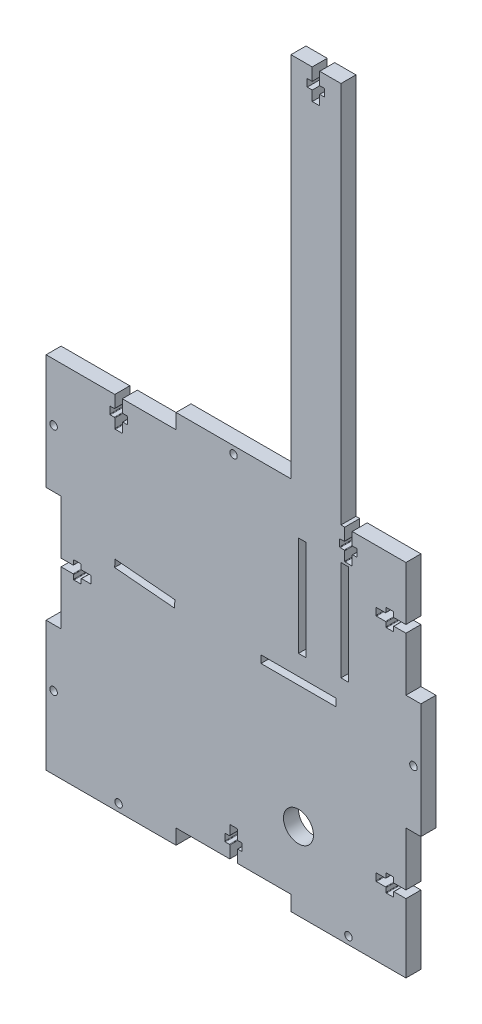
SolidWorks part; units mm, degrees
ref_plane "Front Plane" through (0, 0, 0) normal (0, 0, 1) x (1, 0, 0)
ref_plane "Top Plane" through (0, 0, 0) normal (0, 1, 0) x (1, 0, 0)
ref_plane "Right Plane" through (0, 0, 0) normal (1, 0, 0) x (0, 0, -1)
sketch "Sketch1" plane through (0, 0, 0) normal (0, 0, 1) x (1, 0, 0)
  line L0 (-69, 69) -> (-23, 69)
  line L5 (-75, -75) -> (75, -75) construction
  line L6 (-75, -75) -> (-75, 75) construction
  line L7 (-75, 75) -> (75, 75) construction
  line L8 (75, -75) -> (75, 75) construction
  line L9 (75, 23) -> (69, 23)
  line L10 (69, -23) -> (75, -23)
  line L11 (-69, -69) -> (69, -69) construction
  line L12 (-69, -69) -> (-69, 69) construction
  line L13 (-69, 69) -> (69, 69) construction
  line L14 (69, -69) -> (69, 69) construction
  line L15 (-69, -69) -> (69, 69) construction
  line L16 (69, -69) -> (69, -23)
  line L17 (-23, 69) -> (-23, 75)
  line L18 (-23, 75) -> (23, 75)
  line L19 (23, 75) -> (23, 69)
  line L20 (23, 69) -> (69, 69)
  line L21 (75, -23) -> (75, 23)
  line L22 (69, 23) -> (69, 69)
  line L23 (-75, 23) -> (-69, 23)
  line L24 (-69, 69) -> (-75, 69)
  line L25 (-75, 69) -> (-75, 23)
  line L26 (69, -69) -> (69, -75)
  line L27 (69, -75) -> (23, -75)
  line L28 (23, -75) -> (23, -69)
  line L29 (23, -69) -> (-23, -69)
  line L30 (-23, -69) -> (-23, -75)
  line L31 (-23, -75) -> (-69, -75)
  line L32 (-69, -75) -> (-69, -69) construction
  line L33 (-69, 23) -> (-69, -23)
  line L34 (-69, -23) -> (-75, -23)
  line L35 (-75, -23) -> (-75, -69)
  line L36 (-75, -69) -> (-69, -69) construction
  line L37 (-46, 69) -> (-46, -75) construction
  line L38 (-69, 69) -> (69, -69) construction
  line L39 (-75, -75) -> (-69, -75)
  line L40 (-75, -75) -> (-75, -69)
  point P0 (0, 0)
  point P6 (-7, -7)
  point P26 (0, -75)
  point P27 (-75, 0)
  dimension "D1" = 150
  dimension "D2" = 150
  dimension "D5" = 46
  dimension "D3" = 6
  dimension "D6" = 6
  dimension "D7" = 6
extrude "Box Side" add sketch "Sketch1" along normal blind 6
sketch "Sketch2" plane through (0, 0, 6) normal (0, 0, 1) x (1, 0, 0)
  line L0 (23, 72) -> (-23, 72) construction
  line L1 (23, 75) -> (23, 69) construction
  line L2 (-23, 69) -> (-23, 75) construction
  line L3 (-46, 69) -> (-46, -75) construction
  line L5 (0, 75) -> (0, 69) construction
  line L6 (-23, 75) -> (23, 75) construction
  line L7 (-69, 69) -> (69, 69) construction
  line L16 (-46, 69) -> (-46, -75) construction
  line L21 (0, -69) -> (0, 69) construction
  line L35 (-69, 69) -> (-23, 69) construction
  line L36 (-44.5, 69) -> (-44.5, 64.2)
  line L37 (-44.3, 64) -> (-42.7, 64)
  line L38 (-42.5, 63.8) -> (-42.5, 61.2)
  line L39 (-42.7, 61) -> (-44.3, 61)
  line L40 (-44.5, 60.8) -> (-44.5, 57.2)
  line L46 (-44.7, 57) -> (-47.3, 57)
  line L48 (-44.5, 69) -> (-47.5, 69)
  line L51 (-47.5, 60.8) -> (-47.5, 57.2)
  line L52 (-49.3, 61) -> (-47.7, 61)
  line L53 (-49.5, 63.8) -> (-49.5, 61.2)
  line L54 (-47.7, 64) -> (-49.3, 64)
  line L55 (-47.5, 69) -> (-47.5, 64.2)
  line L56 (47.5, 69) -> (47.5, 64.2)
  line L57 (47.7, 64) -> (49.3, 64)
  line L58 (49.5, 63.8) -> (49.5, 61.2)
  line L59 (49.3, 61) -> (47.7, 61)
  line L60 (47.5, 60.8) -> (47.5, 57.2)
  line L61 (44.5, 69) -> (47.5, 69)
  line L62 (44.7, 57) -> (47.3, 57)
  line L63 (44.5, 60.8) -> (44.5, 57.2)
  line L64 (42.7, 61) -> (44.3, 61)
  line L65 (42.5, 63.8) -> (42.5, 61.2)
  line L66 (44.3, 64) -> (42.7, 64)
  line L67 (44.5, 69) -> (44.5, 64.2)
  line L68 (-69, -69) -> (69, 69) construction
  line L69 (-69, -69) -> (69, 69) construction
  line L70 (75, 0) -> (69, 0) construction
  line L71 (72, 23) -> (72, -23) construction
  line L72 (69, 44.5) -> (64.2, 44.5)
  line L73 (64, 44.3) -> (64, 42.7)
  line L74 (63.8, 42.5) -> (61.2, 42.5)
  line L75 (61, 42.7) -> (61, 44.3)
  line L76 (60.8, 44.5) -> (57.2, 44.5)
  line L77 (57, 44.7) -> (57, 47.3)
  line L78 (69, 44.5) -> (69, 47.5)
  line L79 (60.8, 47.5) -> (57.2, 47.5)
  line L80 (61, 49.3) -> (61, 47.7)
  line L81 (63.8, 49.5) -> (61.2, 49.5)
  line L82 (64, 47.7) -> (64, 49.3)
  line L83 (69, 47.5) -> (64.2, 47.5)
  line L84 (69, -47.5) -> (64.2, -47.5)
  line L85 (64, -47.7) -> (64, -49.3)
  line L86 (63.8, -49.5) -> (61.2, -49.5)
  line L87 (61, -49.3) -> (61, -47.7)
  line L88 (60.8, -47.5) -> (57.2, -47.5)
  line L89 (69, -44.5) -> (69, -47.5)
  line L90 (57, -44.7) -> (57, -47.3)
  line L91 (60.8, -44.5) -> (57.2, -44.5)
  line L92 (61, -42.7) -> (61, -44.3)
  line L93 (63.8, -42.5) -> (61.2, -42.5)
  line L94 (64, -44.3) -> (64, -42.7)
  line L95 (69, -44.5) -> (64.2, -44.5)
  line L120 (-69, 69) -> (69, -69) construction
  line L121 (-69, 69) -> (69, -69) construction
  line L122 (-1.5, -69) -> (1.5, -69)
  line L123 (-23, -69) -> (23, -69) construction
  line L124 (1.5, -69) -> (1.5, -64.2)
  line L125 (1.7, -64) -> (3.3, -64)
  line L126 (3.5, -63.8) -> (3.5, -61.2)
  line L127 (3.3, -61) -> (1.7, -61)
  line L128 (1.5, -60.8) -> (1.5, -57.2)
  line L129 (1.3, -57) -> (-1.3, -57)
  line L130 (-1.5, -60.8) -> (-1.5, -57.2)
  line L131 (-3.3, -61) -> (-1.7, -61)
  line L132 (-3.5, -63.8) -> (-3.5, -61.2)
  line L133 (-1.7, -64) -> (-3.3, -64)
  line L134 (-1.5, -69) -> (-1.5, -64.2)
  line L135 (-69, -1.5) -> (-64.2, -1.5)
  line L136 (-64, -1.7) -> (-64, -3.3)
  line L137 (-63.8, -3.5) -> (-61.2, -3.5)
  line L138 (-61, -3.3) -> (-61, -1.7)
  line L139 (-60.8, -1.5) -> (-57.2, -1.5)
  line L140 (-57, 1.3) -> (-57, -1.3)
  line L141 (-60.8, 1.5) -> (-57.2, 1.5)
  line L142 (-61, 3.3) -> (-61, 1.7)
  line L143 (-63.8, 3.5) -> (-61.2, 3.5)
  line L144 (-64, 1.7) -> (-64, 3.3)
  line L145 (-69, 1.5) -> (-64.2, 1.5)
  line L146 (-69, -1.5) -> (-69, 1.5)
  line L147 (-69, -72) -> (-23, -72) construction
  line L148 (-23, 69) -> (-75, 69) construction
  line L149 (-23, -75) -> (-23, -69) construction
  line L150 (-69, -69) -> (-69, -75) construction
  line L151 (-75, -75) -> (-23, -75) construction
  circle A0 centre (0, 72) radius 1.5
  arc A1 (-44.5, 57.2) -> (-44.7, 57) centre (-44.7, 57.2) cw
  arc A2 (-44.3, 61) -> (-44.5, 60.8) centre (-44.3, 60.8) ccw
  arc A3 (-42.5, 61.2) -> (-42.7, 61) centre (-42.7, 61.2) cw
  arc A4 (-42.7, 64) -> (-42.5, 63.8) centre (-42.7, 63.8) cw
  arc A5 (-44.5, 64.2) -> (-44.3, 64) centre (-44.3, 64.2) ccw
  arc A6 (-47.5, 64.2) -> (-47.7, 64) centre (-47.7, 64.2) cw
  arc A7 (-49.3, 64) -> (-49.5, 63.8) centre (-49.3, 63.8) ccw
  arc A8 (-49.5, 61.2) -> (-49.3, 61) centre (-49.3, 61.2) ccw
  arc A9 (-47.7, 61) -> (-47.5, 60.8) centre (-47.7, 60.8) cw
  arc A10 (-47.5, 57.2) -> (-47.3, 57) centre (-47.3, 57.2) ccw
  arc A11 (47.5, 57.2) -> (47.3, 57) centre (47.3, 57.2) cw
  arc A12 (47.7, 61) -> (47.5, 60.8) centre (47.7, 60.8) ccw
  arc A13 (49.5, 61.2) -> (49.3, 61) centre (49.3, 61.2) cw
  arc A14 (49.3, 64) -> (49.5, 63.8) centre (49.3, 63.8) cw
  arc A15 (47.5, 64.2) -> (47.7, 64) centre (47.7, 64.2) ccw
  arc A16 (44.5, 64.2) -> (44.3, 64) centre (44.3, 64.2) cw
  arc A17 (42.7, 64) -> (42.5, 63.8) centre (42.7, 63.8) ccw
  arc A18 (42.5, 61.2) -> (42.7, 61) centre (42.7, 61.2) ccw
  arc A19 (44.3, 61) -> (44.5, 60.8) centre (44.3, 60.8) cw
  arc A20 (44.5, 57.2) -> (44.7, 57) centre (44.7, 57.2) ccw
  arc A21 (57.2, 44.5) -> (57, 44.7) centre (57.2, 44.7) cw
  arc A22 (61, 44.3) -> (60.8, 44.5) centre (60.8, 44.3) ccw
  arc A23 (61.2, 42.5) -> (61, 42.7) centre (61.2, 42.7) cw
  arc A24 (64, 42.7) -> (63.8, 42.5) centre (63.8, 42.7) cw
  arc A25 (64.2, 44.5) -> (64, 44.3) centre (64.2, 44.3) ccw
  arc A26 (64.2, 47.5) -> (64, 47.7) centre (64.2, 47.7) cw
  arc A27 (64, 49.3) -> (63.8, 49.5) centre (63.8, 49.3) ccw
  arc A28 (61.2, 49.5) -> (61, 49.3) centre (61.2, 49.3) ccw
  arc A29 (61, 47.7) -> (60.8, 47.5) centre (60.8, 47.7) cw
  arc A30 (57.2, 47.5) -> (57, 47.3) centre (57.2, 47.3) ccw
  arc A31 (57.2, -47.5) -> (57, -47.3) centre (57.2, -47.3) cw
  arc A32 (61, -47.7) -> (60.8, -47.5) centre (60.8, -47.7) ccw
  arc A33 (61.2, -49.5) -> (61, -49.3) centre (61.2, -49.3) cw
  arc A34 (64, -49.3) -> (63.8, -49.5) centre (63.8, -49.3) cw
  arc A35 (64.2, -47.5) -> (64, -47.7) centre (64.2, -47.7) ccw
  arc A36 (64.2, -44.5) -> (64, -44.3) centre (64.2, -44.3) cw
  arc A37 (64, -42.7) -> (63.8, -42.5) centre (63.8, -42.7) ccw
  arc A38 (61.2, -42.5) -> (61, -42.7) centre (61.2, -42.7) ccw
  arc A39 (61, -44.3) -> (60.8, -44.5) centre (60.8, -44.3) cw
  arc A40 (57.2, -44.5) -> (57, -44.7) centre (57.2, -44.7) ccw
  circle A41 centre (72, 0) radius 1.5
  arc A62 (1.5, -57.2) -> (1.3, -57) centre (1.3, -57.2) ccw
  arc A63 (1.7, -61) -> (1.5, -60.8) centre (1.7, -60.8) cw
  arc A64 (3.5, -61.2) -> (3.3, -61) centre (3.3, -61.2) ccw
  arc A65 (3.3, -64) -> (3.5, -63.8) centre (3.3, -63.8) ccw
  arc A66 (1.5, -64.2) -> (1.7, -64) centre (1.7, -64.2) cw
  arc A67 (-1.5, -64.2) -> (-1.7, -64) centre (-1.7, -64.2) ccw
  arc A68 (-3.3, -64) -> (-3.5, -63.8) centre (-3.3, -63.8) cw
  arc A69 (-3.5, -61.2) -> (-3.3, -61) centre (-3.3, -61.2) cw
  arc A70 (-1.7, -61) -> (-1.5, -60.8) centre (-1.7, -60.8) ccw
  arc A71 (-1.5, -57.2) -> (-1.3, -57) centre (-1.3, -57.2) cw
  arc A72 (-57.2, -1.5) -> (-57, -1.3) centre (-57.2, -1.3) ccw
  arc A73 (-61, -1.7) -> (-60.8, -1.5) centre (-60.8, -1.7) cw
  arc A74 (-61.2, -3.5) -> (-61, -3.3) centre (-61.2, -3.3) ccw
  arc A75 (-64, -3.3) -> (-63.8, -3.5) centre (-63.8, -3.3) ccw
  arc A76 (-64.2, -1.5) -> (-64, -1.7) centre (-64.2, -1.7) cw
  arc A77 (-64.2, 1.5) -> (-64, 1.7) centre (-64.2, 1.7) ccw
  arc A78 (-64, 3.3) -> (-63.8, 3.5) centre (-63.8, 3.3) cw
  arc A79 (-61.2, 3.5) -> (-61, 3.3) centre (-61.2, 3.3) cw
  arc A80 (-61, 1.7) -> (-60.8, 1.5) centre (-60.8, 1.7) ccw
  arc A81 (-57.2, 1.5) -> (-57, 1.3) centre (-57.2, 1.3) cw
  circle A82 centre (-46, -72) radius 1.5
  circle A83 centre (46, -72) radius 1.5
  circle A84 centre (-72, 46) radius 1.5
  circle A85 centre (-72, -46) radius 1.5
  point P6 (0, 72)
  point P38 (0, 0)
  point P56 (-46, 57)
  point P88 (46, 57)
  point P161 (57, 46)
  point P162 (57, -46)
  point P198 (0, -57)
  point P231 (-57, 0)
  point P234 (-42.5, 62.5)
  dimension "D1" = 3
  dimension "D2" = 0.2
  dimension "D8" = 0.2
  dimension "D14" = 3
  dimension "D4" = 3
  dimension "D7" = 1.5
  dimension "D10" = 3
  dimension "D12" = 1.5
  dimension "D9" = 12
  dimension "D11" = 5
  dimension "D13" = 7
  dimension "D3" = 12
  dimension "D5" = 7
  dimension "D6" = 5
extrude "Screw Cut-outs" cut sketch "Sketch2" against normal through all
sketch "Bearing Hole" plane through (0, 0, 6) normal (0, 0, 1) x (1, 0, 0)
  line L0 (20, -69) -> (50020, -69) construction
  line L1 (69, -44.5) -> (69, -23) construction
  line L4 (26, -41) -> (50026, -41) construction
  line L5 (26.5774, -47) -> (50026.5774, -47) construction
  line L8 (29, -52) -> (29, -50052) construction
  circle A0 centre (26, -44) radius 3 construction
  circle A1 centre (26, -54) radius 15 construction
  circle A2 centre (26, -44) radius 6
  dimension "D2" = 6
  dimension "D4" = 30
  dimension "D5" = 12
  dimension "D1" = 7
  dimension "D3" = 43
extrude "Shaft Hole" cut sketch "Bearing Hole" against normal through all
sketch "Sketch4" plane through (0, 0, 0) normal (0, 0, -1) x (-1, 0, 0)
  line L0 (-72, 1.5) -> (49928, 1.5) construction
  line L1 (-41, 8) -> (-11, 8)
  line L2 (-41, 8) -> (-41, 5)
  line L3 (-41, 5) -> (-11, 5)
  line L4 (-11, 8) -> (-11, 5)
  line L5 (-75, -23) -> (-75, 23) construction
  line L6 (-69, 23) -> (-69, 44.5) construction
  line L7 (-46, 56) -> (-43, 56)
  line L8 (-46, 56) -> (-46, 16)
  line L9 (-46, 16) -> (-43, 16)
  line L10 (-43, 56) -> (-43, 16)
  line L11 (-29, 56) -> (-26, 56)
  line L12 (-29, 56) -> (-29, 16)
  line L13 (-29, 16) -> (-26, 16)
  line L14 (-26, 56) -> (-26, 16)
  line L15 (-44.5, 69) -> (-23, 69) construction
  circle A1 centre (-72, 0) radius 1.5 construction
  point P18 (-29, 36)
  dimension "D1" = 3.5
  dimension "D2" = 30
  dimension "D3" = 3
  dimension "D4" = 34
  dimension "D5" = 14
  dimension "D6" = 23
  dimension "D7" = 13
  dimension "D8" = 3
  dimension "D9" = 40
extrude "Grooves" cut sketch "Sketch4" against normal up to surface (6 mm away) up to face at (32, -44, 6)
sketch "Sketch5" plane through (0, 69, 0) normal (0, 1, 0) x (1, 0, 0)
  line L0 (69, 0) -> (47.5, 0) construction
  line L1 (23, -6) -> (43, -6)
  line L2 (23, -6) -> (23, 0)
  line L3 (23, 0) -> (43, 0)
  line L4 (43, -6) -> (43, 0)
  line L5 (75, -6) -> (75, 0) construction
  dimension "D1" = 32
extrude "Boss-Extrude1" add sketch "Sketch5" along normal blind 153
sketch "Sketch6" plane through (0, 0, 0) normal (0, 0, -1) x (-1, 0, 0)
  line L0 (-34.5, 222) -> (-34.5, 217)
  line L1 (-43, 222) -> (-23, 222) construction
  line L2 (-34.5, 217) -> (-36.5, 217)
  line L3 (-36.5, 217) -> (-36.5, 214)
  line L4 (-36.5, 214) -> (-34.5, 214)
  line L5 (-34.5, 214) -> (-34.5, 210)
  line L6 (-34.5, 210) -> (-31.5, 210)
  line L7 (-31.5, 210) -> (-31.5, 214)
  line L8 (-31.5, 214) -> (-29.5, 214)
  line L9 (-29.5, 214) -> (-29.5, 217)
  line L10 (-29.5, 217) -> (-31.5, 217)
  line L11 (-31.5, 217) -> (-31.5, 222)
  line L12 (-34.5, 222) -> (-31.5, 222)
  line L13 (-29.5, 214) -> (-36.5, 214)
  point P4 (-33, 210)
  point P16 (-33, 222)
  point P17 (-33, 214)
  point P18 (-33, 222)
  dimension "D1" = 3
  dimension "D2" = 7
  dimension "D3" = 5
  dimension "D4" = 12
  dimension "D5" = 3
extrude "Cut-Extrude1" cut sketch "Sketch6" against normal through all contours L13 L8 L9 L10 L11 L12 L0 L2 L3 L4 | L7 L13 L5 L6
sketch "Sketch7" plane through (0, 0, 0) normal (0, 0, -1) x (-1, 0, 0)
  line L4 (2, 40.5315) -> (2, -49959.4685) construction
  line L6 (69, 23) -> (69, 1.5) construction
  line L8 (22.5921, 19.3161) -> (4380.3792, -49790.4188) construction
  line L9 (2, 8) -> (23.4182, 9.8738) construction
  line L10 (23.4182, 9.8738) -> (23.6797, 6.8853)
  line L11 (23.6797, 6.8853) -> (47.5883, 8.977)
  line L12 (47.5883, 8.977) -> (47.3269, 11.9656)
  line L13 (47.3269, 11.9656) -> (23.4182, 9.8738)
  line L14 (23, 69) -> (44.5, 69) construction
  dimension "D1" = 67
  dimension "D2" = 5
  dimension "D3" = 21.5
  dimension "D4" = 24
  dimension "D5" = 3
  dimension "D6" = 61
extrude "Cut-Extrude2" cut sketch "Sketch7" against normal through all
equation "\"filletRadius\"=0.2"
equation "\"D8@Sketch2\"=\"filletRadius\""
equation "\"D2@Sketch2\"=\"filletRadius\""
equation "\"fingerWidth\"= 46"
equation "\"D5@Sketch1\"=\"fingerWidth\""
equation "\"wallThickness\"= 6"
equation "\"D3@Sketch1\" = \"wallThickness\""
equation "\"D6@Sketch1\" = \"wallThickness\""
equation "\"D7@Sketch1\" = \"wallThickness\""
equation "\"D1@Box Side\" = \"wallThickness\""
equation "\"M3\"= 3"
equation "\"D14@Sketch2\"=\"M3\""
equation "\"D1@Sketch2\"=\"M3\""
equation "\"D12@Sketch2\"=\"M3\"/2"
equation "\"nutThickness\"=3"
equation "\"D10@Sketch2\" = \"nutThickness\""
equation "\"boltLength\"= 12"
equation "\"D9@Sketch2\" = \"boltLength\""
equation "\"distanceToNut\"= 5"
equation "\"D11@Sketch2\" = \"distanceToNut\""
equation "\"D13@Sketch2\" = \"nutWidth\""
equation "\"D7@Sketch2\"=\"M3\"/2"
equation "\"D4@Sketch2\" = \"nutThickness\""
equation "\"D3@Sketch2\" = \"boltLength\""
equation "\"D5@Sketch2\" = \"nutWidth\""
equation "\"D6@Sketch2\" = \"distanceToNut\""
equation "\"sideLength\"=150"
equation "\"D1@Sketch1\"=\"sideLength\""
equation "\"D2@Sketch1\"=\"sideLength\""
equation "\"nutWidth\"=7"
equation "\"D1@Sketch6\"=\"M3\""
equation "\"D2@Sketch6\"=\"nutWidth\""
equation "\"D3@Sketch6\"=\"distanceToNut\""
equation "\"D4@Sketch6\"=\"boltLength\""
equation "\"D5@Sketch6\"=\"nutThickness\""
